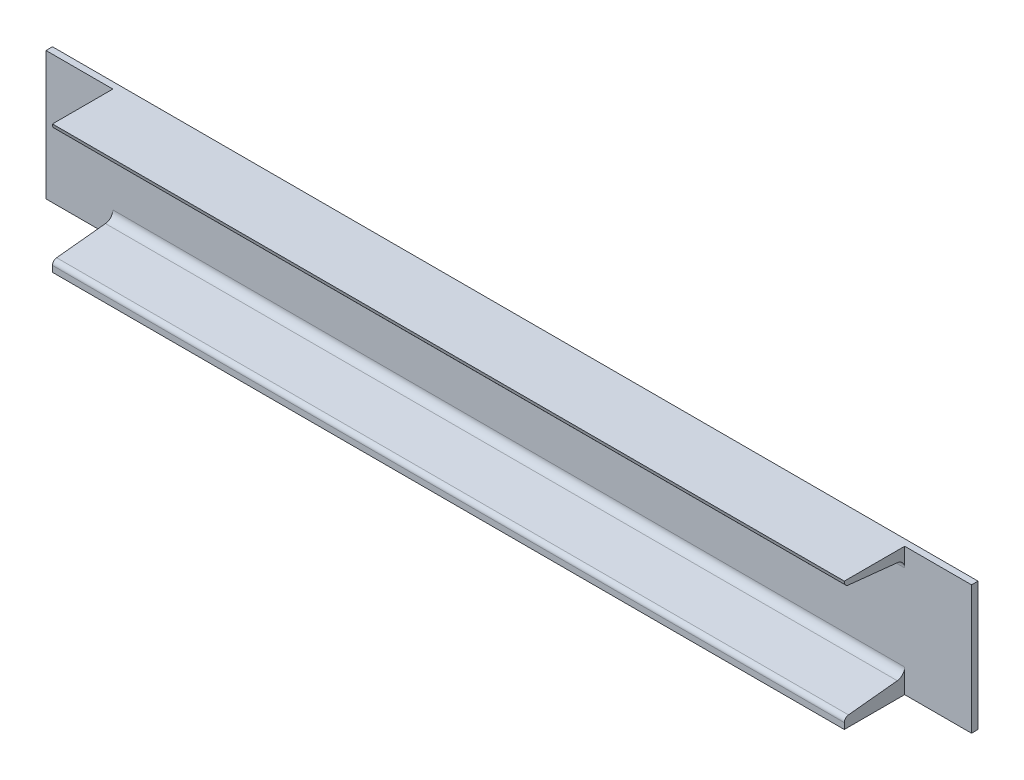
SolidWorks part; units mm, degrees
ref_plane "Front Plane" through (0, 0, 0) normal (0, 0, 1) x (1, 0, 0)
ref_plane "Top Plane" through (0, 0, 0) normal (0, 1, 0) x (1, 0, 0)
ref_plane "Right Plane" through (0, 0, 0) normal (1, 0, 0) x (0, 0, -1)
sketch "Sketch1" plane through (0, 0, 0) normal (0, 1, 0) x (1, 0, 0)
  line L0 (0, 0) -> (-900, 0)
  dimension "D1" = 900
other "C channel 120 X 12(1)"
ref_plane "Plane1" through (0, 0, 0) normal (-1, 0, 0) x (0, 0, 1)
sketch "Sketch12" plane through (0, 0, 0) normal (-1, 0, 0) x (0, 0, 1)
  line L0 (65, 125) -> (0, 125)
  line L1 (65, 0) -> (0, 0)
  line L2 (0, 125) -> (0, 0)
  line L6 (65, 125) -> (65, 124.1647)
  line L7 (65, 0) -> (65, 5.8453)
  line L12 (6.3, 106.74) -> (6.3, 23.27)
  line L17 (13.4638, 114.6962) -> (60.9704, 119.6893)
  line L18 (13.4638, 15.3138) -> (60.9704, 10.3207)
  arc A0 (60.9704, 119.6893) -> (65, 124.1647) centre (60.5, 124.1647) ccw
  arc A1 (60.9704, 10.3207) -> (65, 5.8453) centre (60.5, 5.8453) cw
  arc A9 (6.3, 23.27) -> (13.4638, 15.3138) centre (14.3, 23.27) ccw
  arc A10 (6.3, 106.74) -> (13.4638, 114.6962) centre (14.3, 106.74) cw
  point P8 (0, 62.5)
  point P9 (6.3, 65.005)
  point P10 (32.5, 125)
  point P11 (32.5, 0)
  point P12 (65, 9.8971)
  point P13 (65, 120.1129)
  point P14 (0, 0)
  dimension "D4" = 4.5
  dimension "RI" = 8
  dimension "D2" = 6
  dimension "D3" = 18.26
  dimension "Depth" = 125
  dimension "BF" = 65
  dimension "TW" = 6.3
  dimension "d1" = 83.47
ref_plane "Plane2" through (0, 0, 0) normal (1, 0, 0) x (0, 0, -1)
sketch "Sketch13" plane through (0, 0, 0) normal (1, 0, 0) x (0, 0, -1)
  line L0 (-6.3, 106.74) -> (-6.3, 128.8665)
  line L1 (-6.3, 128.8665) -> (-71.7073, 128.8665)
  line L2 (-71.7073, 128.8665) -> (-71.7073, -13.8725)
  line L3 (-71.7073, -13.8725) -> (-6.3, -13.8725)
  line L4 (-6.3, -13.8725) -> (-6.3, 106.74)
extrude "Cut-Extrude1" cut sketch "Sketch13" against normal blind 65
ref_plane "Plane3" through (-450, 0, 0) normal (1, 0, 0) x (0, 0, -1)
mirror "Mirror1" about plane through (-450, 0, 0) normal (1, 0, 0) of "Cut-Extrude1"
